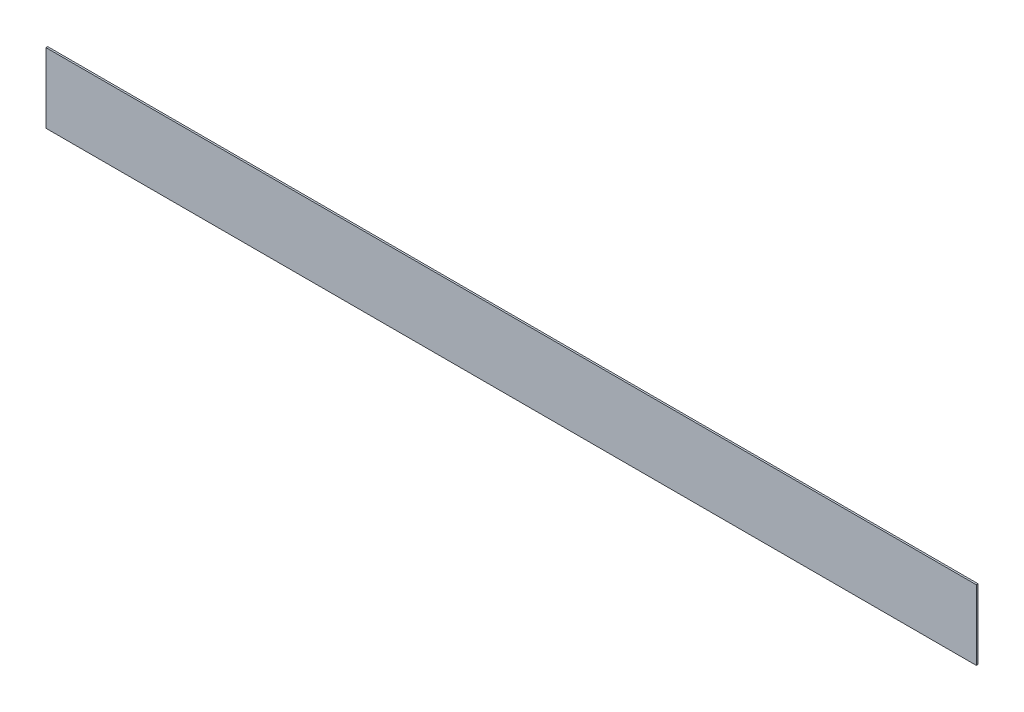
SolidWorks part; units mm, degrees
ref_plane "Front Plane" through (0, 0, 0) normal (0, 0, 1) x (1, 0, 0)
ref_plane "Top Plane" through (0, 0, 0) normal (0, 1, 0) x (1, 0, 0)
ref_plane "Right Plane" through (0, 0, 0) normal (1, 0, 0) x (0, 0, -1)
sketch "Sketch1" plane through (0, 0, 0) normal (0, 0, 1) x (1, 0, 0)
  line L1 (0, 0) -> (1065, 0)
  line L2 (0, 0) -> (0, -80)
  line L3 (0, -80) -> (1065, -80)
  line L4 (1065, 0) -> (1065, -80)
  dimension "D1" = 1065
  dimension "D2" = 80
extrude "Boss-Extrude1" add sketch "Sketch1" along normal blind 2
